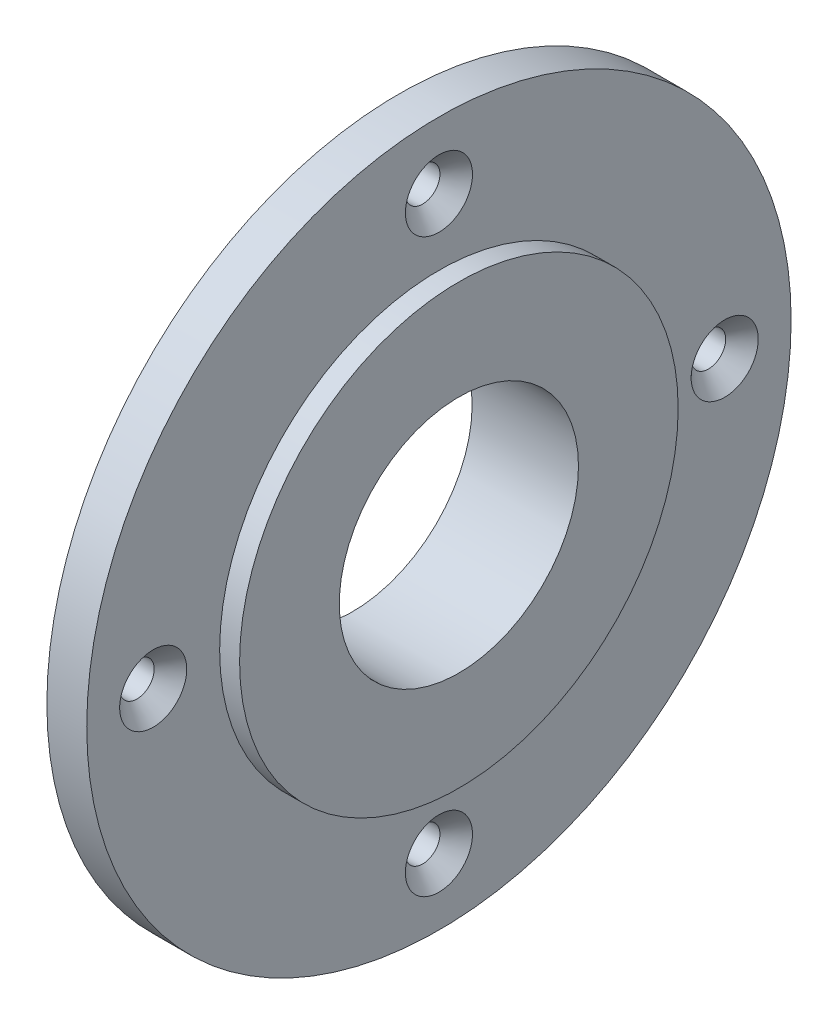
SolidWorks part; units mm, degrees
ref_plane "Front Plane" through (0, 0, 0) normal (0, 0, 1) x (1, 0, 0)
ref_plane "Top Plane" through (0, 0, 0) normal (0, 1, 0) x (1, 0, 0)
ref_plane "Right Plane" through (0, 0, 0) normal (1, 0, 0) x (0, 0, -1)
sketch "Sketch2" plane through (0, 0, 0) normal (0, 0, 1) x (1, 0, 0)
  line L0 (-192.9056, 33) -> (-195.9056, 33)
  line L1 (-195.9056, 33) -> (-195.9056, 53)
  line L2 (-195.9056, 53) -> (-201.9056, 53)
  line L3 (-201.9056, 53) -> (-201.9056, 21)
  line L4 (-208.9056, 18) -> (-192.9056, 18)
  line L5 (-192.9056, 18) -> (-192.9056, 33)
  line L6 (0, 0) -> (-61.0884, 0) construction
  line L7 (-202.4056, 24.5008) -> (-202.4056, 42.4269) construction
  line L8 (-201.9056, 21) -> (-208.9056, 21)
  line L9 (-208.9056, 21) -> (-208.9056, 18)
  line L14 (-220.9056, -21) -> (-220.9056, 21) construction
  dimension "D1" = 6
  dimension "D2" = 42
  dimension "D3" = 36
  dimension "D5" = 3
  dimension "D6" = 106
  dimension "D7" = 15
  dimension "D8" = 12
  dimension "D4" = 0.5
revolve "Revolve1" add sketch "Sketch2" angle 360 about L6
sketch "Sketch3" plane through (-195.9056, 0, 0) normal (1, 0, 0) x (0, 0, -1)
  circle A0 centre (0, 0) radius 43 construction
  circle A1 centre (0, 43) radius 3.3774
  dimension "D1" = 86
hole_wizard "CSK for M5 Countersunk Flat Head Screw1" positions "Sketch4" profile "Sketch5" countersink size "M5" standard "ISO" end condition through all
sketch "Sketch4" plane through (-195.9056, 0, 0) normal (1, 0, 0) x (0, 0, -1)
  point P0 (0, 43)
sketch "Sketch5" plane through (-195.9056, 43, 0) normal (0, 1, 0) x (0, 0, -1)
  line L0 (0, 0) -> (0, 13)
  line L1 (0, 13) -> (2.6, 13)
  line L2 (2.6, 13) -> (2.6, 2.45)
  line L3 (2.6, 2.45) -> (5.05, 0)
  line L5 (5.05, 0) -> (0, 0)
  line L6 (-2.6, 2.45) -> (-5.05, 0) construction
  line L11 (0, -6.35) -> (0, 107.95) construction
  dimension "Thru Hole Dia." = 5.2
  dimension "Thru Hole Depth" = 13
  dimension "Near C'Sink Dia." = 10.1
  dimension "Near C'Sink Angle" = 90
pattern_circular "CirPattern1" count 4 over 360 about axis through (0, 0, 0) along (1, 0, 0) of "CSK for M5 Countersunk Flat Head Screw1"
equation "\"l-x_vis_flasque_rouleau\"=4"
equation "\"D1@Sketch2\"=\"l-x_vis_flasque_rouleau\"+2"
equation "\"d_ext_rouleau\"= 120"
equation "\"epaisseur_rouleau\"=80"
equation "\"alesage-rouleau\"= 52"
equation "\"jeu_dent_rouleau\"= 2"
equation "\"profondeur_dent_rouleau\"=4"
equation "\"n_dent_roueau\"= 15"
equation "\"B_roulement_rouleau\"= 12"
equation "\"F_anneau_alesage_rouleau\"=1.85"
equation "\"G_anneau_alesage_rouleau\"=47.5"
equation "\"K_anneau_alesage_rouleau\"=3.75"
equation "\"d_vis_flasque_rouleau\"=5"
equation "\"D2@Sketch2\" = \"d_ext_roulement_rouleau\""
equation "\"D3@Sketch2\"= \"d_ext_roulement_rouleau\" - 6"
equation "\"D8@Sketch2\"=\"B_roulement_rouleau\""
equation "\"g_anneau_arbre_rouleau\"=19"
equation "\"f_anneau_arbre_rouleau\"=1.3"
equation "\"k_anneau_arbre_rouleau\"=1.5"
equation "\"h_matrice\"= 15"
equation "\"d_matrice\"= 250"
equation "\"d_granulat\"= 8"
equation "\"zone_vide_matrice\" = 70"
equation "\"d_alesage_matrice\"=50"
equation "\"a_clavette_alesage_matrice\"=16"
equation "\"entrax_vis_rouleau\"=86"
equation "\"d_ext_roulement_rouleau\"= 42"
equation "\"d_int_roulement_rouleau\"= 20"
